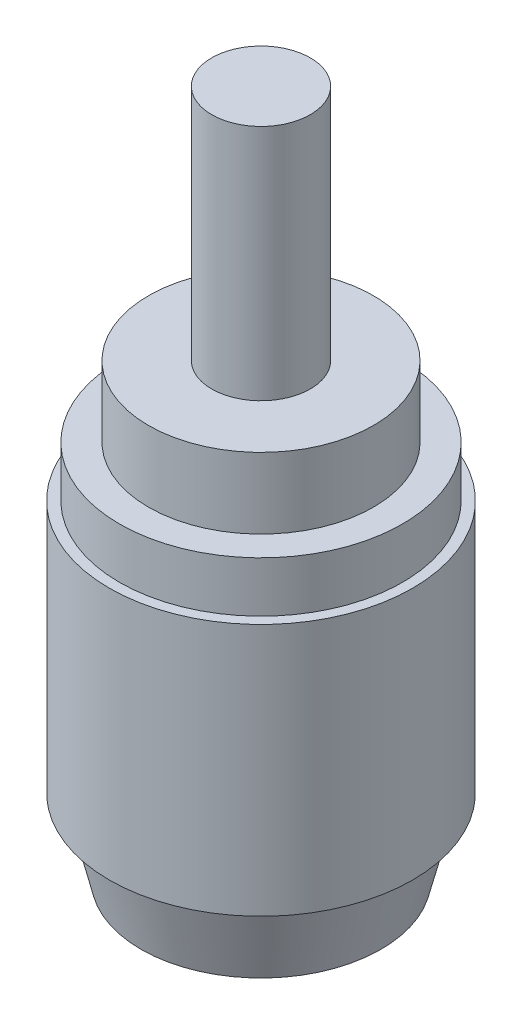
SolidWorks part; units mm, degrees
material "镀铬不锈钢"
ref_plane "前视基准面" through (0, 0, 0) normal (0, 0, 1) x (1, 0, 0)
ref_plane "上视基准面" through (0, 0, 0) normal (0, 1, 0) x (1, 0, 0)
ref_plane "右视基准面" through (0, 0, 0) normal (1, 0, 0) x (0, 0, -1)
sketch "草图1" plane through (0, 0, 0) normal (0, 0, 1) x (1, 0, 0)
  line L0 (0, 15.734) -> (0, -3.7336) construction
  line L1 (0, 0) -> (4.75, 0)
  line L2 (4.75, 0) -> (5.5, 3)
  line L3 (6, 3) -> (6, 13)
  line L4 (6, 13) -> (5.6, 13)
  line L5 (5.6, 13) -> (5.6, 15)
  line L6 (5.6, 15) -> (0, 15)
  line L7 (5.5, 3) -> (6, 3)
  line L8 (0, 0) -> (0, 15)
  dimension "D1" = 4.75
  dimension "D2" = 6
  dimension "D3" = 5.5
  dimension "D4" = 3
  dimension "D5" = 10
  dimension "D6" = 5.6
  dimension "D7" = 2
revolve "旋转1" add sketch "草图1" angle 360 about L0
sketch "草图2" plane through (0, 15, 0) normal (0, 1, 0) x (1, 0, 0)
  circle A0 centre (0, 0) radius 4.45
  dimension "D1" = 8.9
extrude "凸台-拉伸1" add sketch "草图2" along normal blind 2.8
sketch "草图3" plane through (0, 17.8, 0) normal (0, 1, 0) x (1, 0, 0)
  circle A0 centre (0, 0) radius 1.95
  dimension "D1" = 3.9
extrude "凸台-拉伸2" add sketch "草图3" along normal blind 9.4
